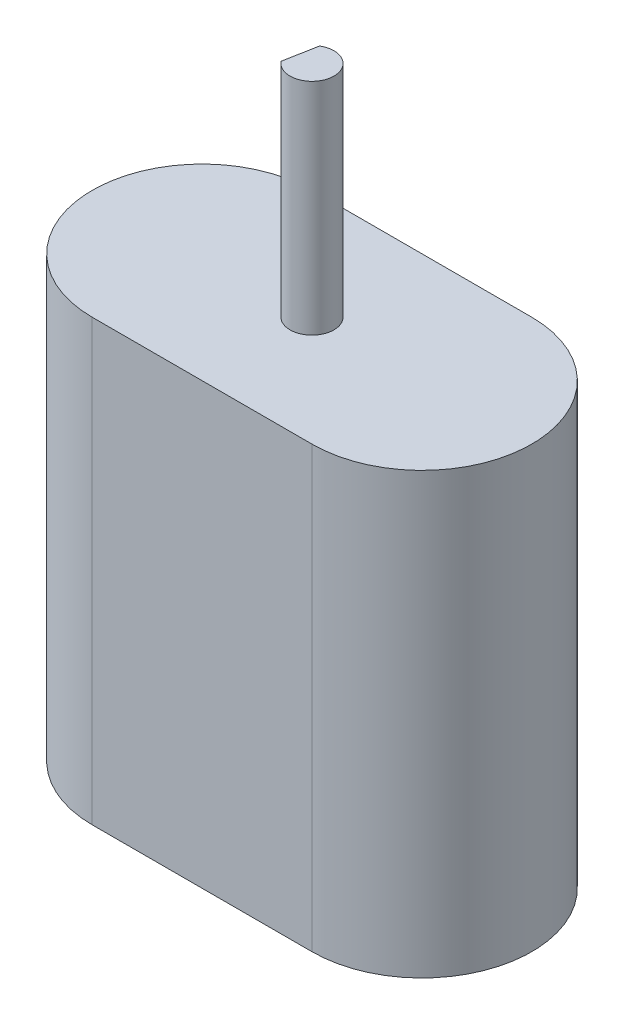
SolidWorks part; units mm, degrees
ref_plane "Front Plane" through (0, 0, 0) normal (0, 0, 1) x (1, 0, 0)
ref_plane "Top Plane" through (0, 0, 0) normal (0, 1, 0) x (1, 0, 0)
ref_plane "Right Plane" through (0, 0, 0) normal (1, 0, 0) x (0, 0, -1)
sketch "Sketch1" plane through (0, 0, 0) normal (0, 1, 0) x (1, 0, 0)
  line L0 (0, 0) -> (10, 0) construction
  line L5 (0, 5) -> (10, 5)
  line L6 (0, -5) -> (10, -5)
  arc A0 (0, 5) -> (0, -5) centre (0, 0) ccw
  arc A1 (10, -5) -> (10, 5) centre (10, 0) ccw
  point P2 (5, 0)
  dimension "D1" = 10
  dimension "D2" = 10
extrude "Boss-Extrude1" add sketch "Sketch1" along normal blind 20
sketch "Sketch2" plane through (0, 20, 0) normal (0, 1, 0) x (1, 0, 0)
  line L0 (0, 0) -> (10, 0) construction
  line L1 (5, 5) -> (5, -5) construction
  line L2 (10, 5) -> (0, 5) construction
  line L3 (0, -5) -> (10, -5) construction
  point P10 (5, 0)
sketch "Sketch4" plane through (0, 20, 0) normal (0, 1, 0) x (1, 0, 0)
  line L0 (5, 5) -> (5, -5) construction
  circle A0 centre (5, 0) radius 1
  dimension "D1" = 2
extrude "Boss-Extrude2" add sketch "Sketch4" along normal blind 10
sketch "Sketch5" plane through (0, 30, 0) normal (0, 1, 0) x (1, 0, 0)
  line L0 (4.4885, 0.8593) -> (4.2114, -0.6149)
  arc A0 (4.2114, -0.6149) -> (4.4885, 0.8593) centre (5, 0) cw
  circle A1 centre (5, 0) radius 1 construction
  dimension "D2" = 1
  dimension "D1" = 1.5
extrude "Cut-Extrude1" cut sketch "Sketch5" against normal blind 10
